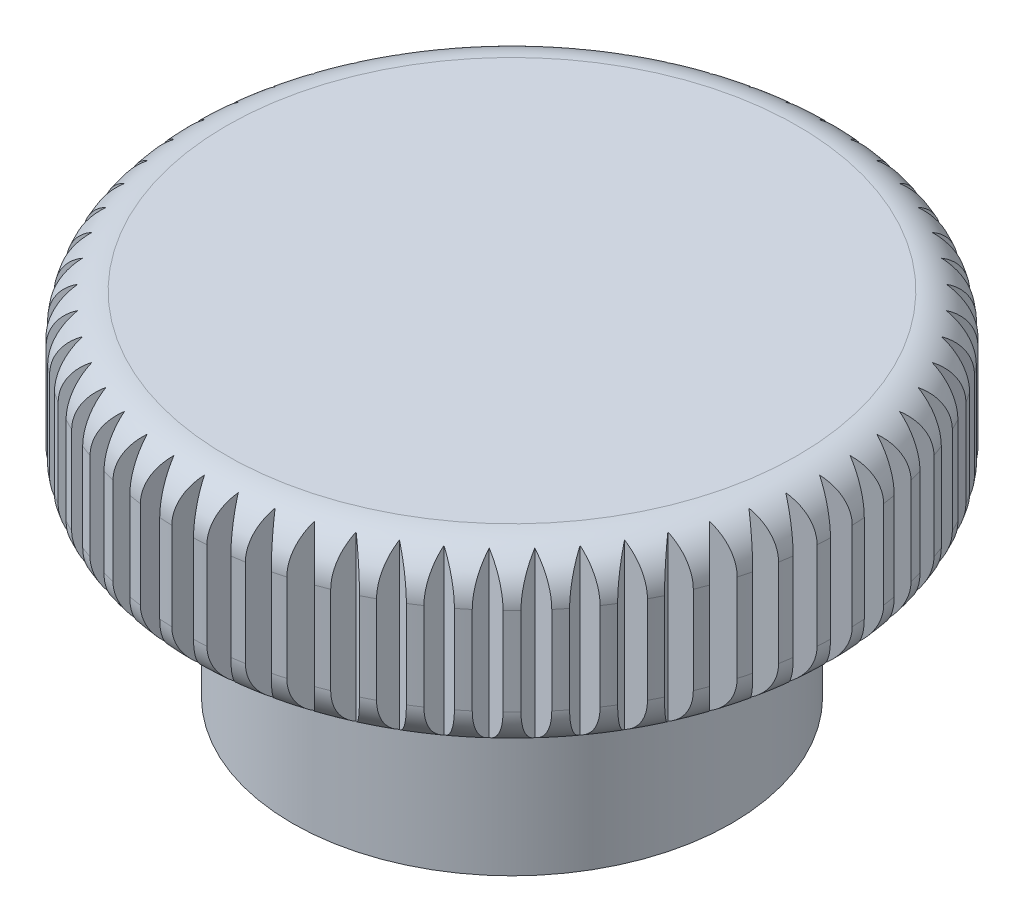
SolidWorks part; units mm, degrees
ref_plane "前视基准面" through (0, 0, 0) normal (0, 0, 1) x (1, 0, 0)
ref_plane "上视基准面" through (0, 0, 0) normal (0, 1, 0) x (1, 0, 0)
ref_plane "右视基准面" through (0, 0, 0) normal (1, 0, 0) x (0, 0, -1)
sketch "草图1" plane through (0, 0, 0) normal (0, 0, 1) x (1, 0, 0)
  line L0 (0, 0) -> (0, -8)
  line L1 (0, -8) -> (5, -8)
  line L2 (0, 0) -> (6.5, 0)
  line L3 (7.5, -1) -> (7.5, -3)
  line L4 (6.5, -4) -> (6, -4)
  line L5 (5, -5) -> (5, -8)
  arc A0 (6.5, 0) -> (7.5, -1) centre (6.5, -1) cw
  arc A1 (6, -4) -> (5, -5) centre (6, -5) ccw
  arc A2 (7.5, -3) -> (6.5, -4) centre (6.5, -3) cw
  point P9 (7.5, 0)
  point P14 (7.5, -4)
  dimension "D5" = 1
  dimension "D1" = 8
  dimension "D2" = 5
  dimension "D3" = 4
  dimension "D4" = 7.5
revolve "旋转1" add sketch "草图1" angle 360 about L0
sketch "草图2" plane through (0, -8, 0) normal (0, -1, 0) x (1, 0, 0)
  circle A0 centre (0, 0) radius 1.9
  dimension "D1" = 3.8
extrude "切除-拉伸1" cut sketch "草图2" against normal blind 7
sketch "草图3" plane through (0, 0, 0) normal (0, 1, 0) x (1, 0, 0)
  line L0 (0, 0) -> (0, 7.5) construction
  line L1 (0, 7) -> (0.25, 7.5)
  line L2 (0.25, 7.5) -> (-0.25, 7.5)
  line L3 (0, 7) -> (-0.25, 7.5)
  line L4 (0.7317, 6.9617) -> (1.0326, 7.4328)
  line L5 (1.0326, 7.4328) -> (0.5353, 7.485)
  line L6 (0.7317, 6.9617) -> (0.5353, 7.485)
  line L7 (1.4554, 6.847) -> (1.8039, 7.2841)
  line L8 (1.8039, 7.2841) -> (1.3148, 7.3881)
  line L9 (1.4554, 6.847) -> (1.3148, 7.3881)
  line L10 (2.1631, 6.6574) -> (2.5554, 7.0557)
  line L11 (2.5554, 7.0557) -> (2.0799, 7.2102)
  line L12 (2.1631, 6.6574) -> (2.0799, 7.2102)
  line L13 (2.8472, 6.3948) -> (3.2789, 6.7499)
  line L14 (3.2789, 6.7499) -> (2.8221, 6.9533)
  line L15 (2.8472, 6.3948) -> (2.8221, 6.9533)
  line L16 (3.5, 6.0622) -> (3.9665, 6.3702)
  line L17 (3.9665, 6.3702) -> (3.5335, 6.6202)
  line L18 (3.5, 6.0622) -> (3.5335, 6.6202)
  line L19 (4.1145, 5.6631) -> (4.6106, 5.9207)
  line L20 (4.6106, 5.9207) -> (4.2061, 6.2146)
  line L21 (4.1145, 5.6631) -> (4.2061, 6.2146)
  line L22 (4.6839, 5.202) -> (5.2043, 5.4063)
  line L23 (5.2043, 5.4063) -> (4.8327, 5.7409)
  line L24 (4.6839, 5.202) -> (4.8327, 5.7409)
  line L25 (5.202, 4.6839) -> (5.7409, 4.8327)
  line L26 (5.7409, 4.8327) -> (5.4063, 5.2043)
  line L27 (5.202, 4.6839) -> (5.4063, 5.2043)
  line L28 (5.6631, 4.1145) -> (6.2146, 4.2061)
  line L29 (6.2146, 4.2061) -> (5.9207, 4.6106)
  line L30 (5.6631, 4.1145) -> (5.9207, 4.6106)
  line L31 (6.0622, 3.5) -> (6.6202, 3.5335)
  line L32 (6.6202, 3.5335) -> (6.3702, 3.9665)
  line L33 (6.0622, 3.5) -> (6.3702, 3.9665)
  line L34 (6.3948, 2.8472) -> (6.9533, 2.8221)
  line L35 (6.9533, 2.8221) -> (6.7499, 3.2789)
  line L36 (6.3948, 2.8472) -> (6.7499, 3.2789)
  line L37 (6.6574, 2.1631) -> (7.2102, 2.0799)
  line L38 (7.2102, 2.0799) -> (7.0557, 2.5554)
  line L39 (6.6574, 2.1631) -> (7.0557, 2.5554)
  line L40 (6.847, 1.4554) -> (7.3881, 1.3148)
  line L41 (7.3881, 1.3148) -> (7.2841, 1.8039)
  line L42 (6.847, 1.4554) -> (7.2841, 1.8039)
  line L43 (6.9617, 0.7317) -> (7.485, 0.5353)
  line L44 (7.485, 0.5353) -> (7.4328, 1.0326)
  line L45 (6.9617, 0.7317) -> (7.4328, 1.0326)
  line L46 (7, 0) -> (7.5, -0.25)
  line L47 (7.5, -0.25) -> (7.5, 0.25)
  line L48 (7, 0) -> (7.5, 0.25)
  line L49 (6.9617, -0.7317) -> (7.4328, -1.0326)
  line L50 (7.4328, -1.0326) -> (7.485, -0.5353)
  line L51 (6.9617, -0.7317) -> (7.485, -0.5353)
  line L52 (6.847, -1.4554) -> (7.2841, -1.8039)
  line L53 (7.2841, -1.8039) -> (7.3881, -1.3148)
  line L54 (6.847, -1.4554) -> (7.3881, -1.3148)
  line L55 (6.6574, -2.1631) -> (7.0557, -2.5554)
  line L56 (7.0557, -2.5554) -> (7.2102, -2.0799)
  line L57 (6.6574, -2.1631) -> (7.2102, -2.0799)
  line L58 (6.3948, -2.8472) -> (6.7499, -3.2789)
  line L59 (6.7499, -3.2789) -> (6.9533, -2.8221)
  line L60 (6.3948, -2.8472) -> (6.9533, -2.8221)
  line L61 (6.0622, -3.5) -> (6.3702, -3.9665)
  line L62 (6.3702, -3.9665) -> (6.6202, -3.5335)
  line L63 (6.0622, -3.5) -> (6.6202, -3.5335)
  line L64 (5.6631, -4.1145) -> (5.9207, -4.6106)
  line L65 (5.9207, -4.6106) -> (6.2146, -4.2061)
  line L66 (5.6631, -4.1145) -> (6.2146, -4.2061)
  line L67 (5.202, -4.6839) -> (5.4063, -5.2043)
  line L68 (5.4063, -5.2043) -> (5.7409, -4.8327)
  line L69 (5.202, -4.6839) -> (5.7409, -4.8327)
  line L70 (4.6839, -5.202) -> (4.8327, -5.7409)
  line L71 (4.8327, -5.7409) -> (5.2043, -5.4063)
  line L72 (4.6839, -5.202) -> (5.2043, -5.4063)
  line L73 (4.1145, -5.6631) -> (4.2061, -6.2146)
  line L74 (4.2061, -6.2146) -> (4.6106, -5.9207)
  line L75 (4.1145, -5.6631) -> (4.6106, -5.9207)
  line L76 (3.5, -6.0622) -> (3.5335, -6.6202)
  line L77 (3.5335, -6.6202) -> (3.9665, -6.3702)
  line L78 (3.5, -6.0622) -> (3.9665, -6.3702)
  line L79 (2.8472, -6.3948) -> (2.8221, -6.9533)
  line L80 (2.8221, -6.9533) -> (3.2789, -6.7499)
  line L81 (2.8472, -6.3948) -> (3.2789, -6.7499)
  line L82 (2.1631, -6.6574) -> (2.0799, -7.2102)
  line L83 (2.0799, -7.2102) -> (2.5554, -7.0557)
  line L84 (2.1631, -6.6574) -> (2.5554, -7.0557)
  line L85 (1.4554, -6.847) -> (1.3148, -7.3881)
  line L86 (1.3148, -7.3881) -> (1.8039, -7.2841)
  line L87 (1.4554, -6.847) -> (1.8039, -7.2841)
  line L88 (0.7317, -6.9617) -> (0.5353, -7.485)
  line L89 (0.5353, -7.485) -> (1.0326, -7.4328)
  line L90 (0.7317, -6.9617) -> (1.0326, -7.4328)
  line L91 (0, -7) -> (-0.25, -7.5)
  line L92 (-0.25, -7.5) -> (0.25, -7.5)
  line L93 (0, -7) -> (0.25, -7.5)
  line L94 (-0.7317, -6.9617) -> (-1.0326, -7.4328)
  line L95 (-1.0326, -7.4328) -> (-0.5353, -7.485)
  line L96 (-0.7317, -6.9617) -> (-0.5353, -7.485)
  line L97 (-1.4554, -6.847) -> (-1.8039, -7.2841)
  line L98 (-1.8039, -7.2841) -> (-1.3148, -7.3881)
  line L99 (-1.4554, -6.847) -> (-1.3148, -7.3881)
  line L100 (-2.1631, -6.6574) -> (-2.5554, -7.0557)
  line L101 (-2.5554, -7.0557) -> (-2.0799, -7.2102)
  line L102 (-2.1631, -6.6574) -> (-2.0799, -7.2102)
  line L103 (-2.8472, -6.3948) -> (-3.2789, -6.7499)
  line L104 (-3.2789, -6.7499) -> (-2.8221, -6.9533)
  line L105 (-2.8472, -6.3948) -> (-2.8221, -6.9533)
  line L106 (-3.5, -6.0622) -> (-3.9665, -6.3702)
  line L107 (-3.9665, -6.3702) -> (-3.5335, -6.6202)
  line L108 (-3.5, -6.0622) -> (-3.5335, -6.6202)
  line L109 (-4.1145, -5.6631) -> (-4.6106, -5.9207)
  line L110 (-4.6106, -5.9207) -> (-4.2061, -6.2146)
  line L111 (-4.1145, -5.6631) -> (-4.2061, -6.2146)
  line L112 (-4.6839, -5.202) -> (-5.2043, -5.4063)
  line L113 (-5.2043, -5.4063) -> (-4.8327, -5.7409)
  line L114 (-4.6839, -5.202) -> (-4.8327, -5.7409)
  line L115 (-5.202, -4.6839) -> (-5.7409, -4.8327)
  line L116 (-5.7409, -4.8327) -> (-5.4063, -5.2043)
  line L117 (-5.202, -4.6839) -> (-5.4063, -5.2043)
  line L118 (-5.6631, -4.1145) -> (-6.2146, -4.2061)
  line L119 (-6.2146, -4.2061) -> (-5.9207, -4.6106)
  line L120 (-5.6631, -4.1145) -> (-5.9207, -4.6106)
  line L121 (-6.0622, -3.5) -> (-6.6202, -3.5335)
  line L122 (-6.6202, -3.5335) -> (-6.3702, -3.9665)
  line L123 (-6.0622, -3.5) -> (-6.3702, -3.9665)
  line L124 (-6.3948, -2.8472) -> (-6.9533, -2.8221)
  line L125 (-6.9533, -2.8221) -> (-6.7499, -3.2789)
  line L126 (-6.3948, -2.8472) -> (-6.7499, -3.2789)
  line L127 (-6.6574, -2.1631) -> (-7.2102, -2.0799)
  line L128 (-7.2102, -2.0799) -> (-7.0557, -2.5554)
  line L129 (-6.6574, -2.1631) -> (-7.0557, -2.5554)
  line L130 (-6.847, -1.4554) -> (-7.3881, -1.3148)
  line L131 (-7.3881, -1.3148) -> (-7.2841, -1.8039)
  line L132 (-6.847, -1.4554) -> (-7.2841, -1.8039)
  line L133 (-6.9617, -0.7317) -> (-7.485, -0.5353)
  line L134 (-7.485, -0.5353) -> (-7.4328, -1.0326)
  line L135 (-6.9617, -0.7317) -> (-7.4328, -1.0326)
  line L136 (-7, 0) -> (-7.5, 0.25)
  line L137 (-7.5, 0.25) -> (-7.5, -0.25)
  line L138 (-7, 0) -> (-7.5, -0.25)
  line L139 (-6.9617, 0.7317) -> (-7.4328, 1.0326)
  line L140 (-7.4328, 1.0326) -> (-7.485, 0.5353)
  line L141 (-6.9617, 0.7317) -> (-7.485, 0.5353)
  line L142 (-6.847, 1.4554) -> (-7.2841, 1.8039)
  line L143 (-7.2841, 1.8039) -> (-7.3881, 1.3148)
  line L144 (-6.847, 1.4554) -> (-7.3881, 1.3148)
  line L145 (-6.6574, 2.1631) -> (-7.0557, 2.5554)
  line L146 (-7.0557, 2.5554) -> (-7.2102, 2.0799)
  line L147 (-6.6574, 2.1631) -> (-7.2102, 2.0799)
  line L148 (-6.3948, 2.8472) -> (-6.7499, 3.2789)
  line L149 (-6.7499, 3.2789) -> (-6.9533, 2.8221)
  line L150 (-6.3948, 2.8472) -> (-6.9533, 2.8221)
  line L151 (-6.0622, 3.5) -> (-6.3702, 3.9665)
  line L152 (-6.3702, 3.9665) -> (-6.6202, 3.5335)
  line L153 (-6.0622, 3.5) -> (-6.6202, 3.5335)
  line L154 (-5.6631, 4.1145) -> (-5.9207, 4.6106)
  line L155 (-5.9207, 4.6106) -> (-6.2146, 4.2061)
  line L156 (-5.6631, 4.1145) -> (-6.2146, 4.2061)
  line L157 (-5.202, 4.6839) -> (-5.4063, 5.2043)
  line L158 (-5.4063, 5.2043) -> (-5.7409, 4.8327)
  line L159 (-5.202, 4.6839) -> (-5.7409, 4.8327)
  line L160 (-4.6839, 5.202) -> (-4.8327, 5.7409)
  line L161 (-4.8327, 5.7409) -> (-5.2043, 5.4063)
  line L162 (-4.6839, 5.202) -> (-5.2043, 5.4063)
  line L163 (-4.1145, 5.6631) -> (-4.2061, 6.2146)
  line L164 (-4.2061, 6.2146) -> (-4.6106, 5.9207)
  line L165 (-4.1145, 5.6631) -> (-4.6106, 5.9207)
  line L166 (-3.5, 6.0622) -> (-3.5335, 6.6202)
  line L167 (-3.5335, 6.6202) -> (-3.9665, 6.3702)
  line L168 (-3.5, 6.0622) -> (-3.9665, 6.3702)
  line L169 (-2.8472, 6.3948) -> (-2.8221, 6.9533)
  line L170 (-2.8221, 6.9533) -> (-3.2789, 6.7499)
  line L171 (-2.8472, 6.3948) -> (-3.2789, 6.7499)
  line L172 (-2.1631, 6.6574) -> (-2.0799, 7.2102)
  line L173 (-2.0799, 7.2102) -> (-2.5554, 7.0557)
  line L174 (-2.1631, 6.6574) -> (-2.5554, 7.0557)
  line L175 (-1.4554, 6.847) -> (-1.3148, 7.3881)
  line L176 (-1.3148, 7.3881) -> (-1.8039, 7.2841)
  line L177 (-1.4554, 6.847) -> (-1.8039, 7.2841)
  line L178 (-0.7317, 6.9617) -> (-0.5353, 7.485)
  line L179 (-0.5353, 7.485) -> (-1.0326, 7.4328)
  line L180 (-0.7317, 6.9617) -> (-1.0326, 7.4328)
  circle A0 centre (0, 0) radius 7.5 construction
  point P10 (0, 7.5)
  point P16 (0.784, 7.4589)
  point P20 (1.5593, 7.3361)
  point P24 (2.3176, 7.1329)
  point P28 (3.0505, 6.8516)
  point P32 (3.75, 6.4952)
  point P36 (4.4084, 6.0676)
  point P40 (5.0185, 5.5736)
  point P44 (5.5736, 5.0185)
  point P48 (6.0676, 4.4084)
  point P52 (6.4952, 3.75)
  point P56 (6.8516, 3.0505)
  point P60 (7.1329, 2.3176)
  point P64 (7.3361, 1.5593)
  point P68 (7.4589, 0.784)
  point P72 (7.5, 0)
  point P76 (7.4589, -0.784)
  point P80 (7.3361, -1.5593)
  point P84 (7.1329, -2.3176)
  point P88 (6.8516, -3.0505)
  point P92 (6.4952, -3.75)
  point P96 (6.0676, -4.4084)
  point P100 (5.5736, -5.0185)
  point P104 (5.0185, -5.5736)
  point P108 (4.4084, -6.0676)
  point P112 (3.75, -6.4952)
  point P116 (3.0505, -6.8516)
  point P120 (2.3176, -7.1329)
  point P124 (1.5593, -7.3361)
  point P128 (0.784, -7.4589)
  point P132 (0, -7.5)
  point P136 (-0.784, -7.4589)
  point P140 (-1.5593, -7.3361)
  point P144 (-2.3176, -7.1329)
  point P148 (-3.0505, -6.8516)
  point P152 (-3.75, -6.4952)
  point P156 (-4.4084, -6.0676)
  point P160 (-5.0185, -5.5736)
  point P164 (-5.5736, -5.0185)
  point P168 (-6.0676, -4.4084)
  point P172 (-6.4952, -3.75)
  point P176 (-6.8516, -3.0505)
  point P180 (-7.1329, -2.3176)
  point P184 (-7.3361, -1.5593)
  point P188 (-7.4589, -0.784)
  point P192 (-7.5, 0)
  point P196 (-7.4589, 0.784)
  point P200 (-7.3361, 1.5593)
  point P204 (-7.1329, 2.3176)
  point P208 (-6.8516, 3.0505)
  point P212 (-6.4952, 3.75)
  point P216 (-6.0676, 4.4084)
  point P220 (-5.5736, 5.0185)
  point P224 (-5.0185, 5.5736)
  point P228 (-4.4084, 6.0676)
  point P232 (-3.75, 6.4952)
  point P236 (-3.0505, 6.8516)
  point P240 (-2.3176, 7.1329)
  point P244 (-1.5593, 7.3361)
  point P248 (-0.784, 7.4589)
  point P249 (0, 0)
  dimension "D1" = 0.5
  dimension "D2" = 0.5
  dimension "D3" = 60
extrude "切除-拉伸2" cut sketch "草图3" against normal through all
